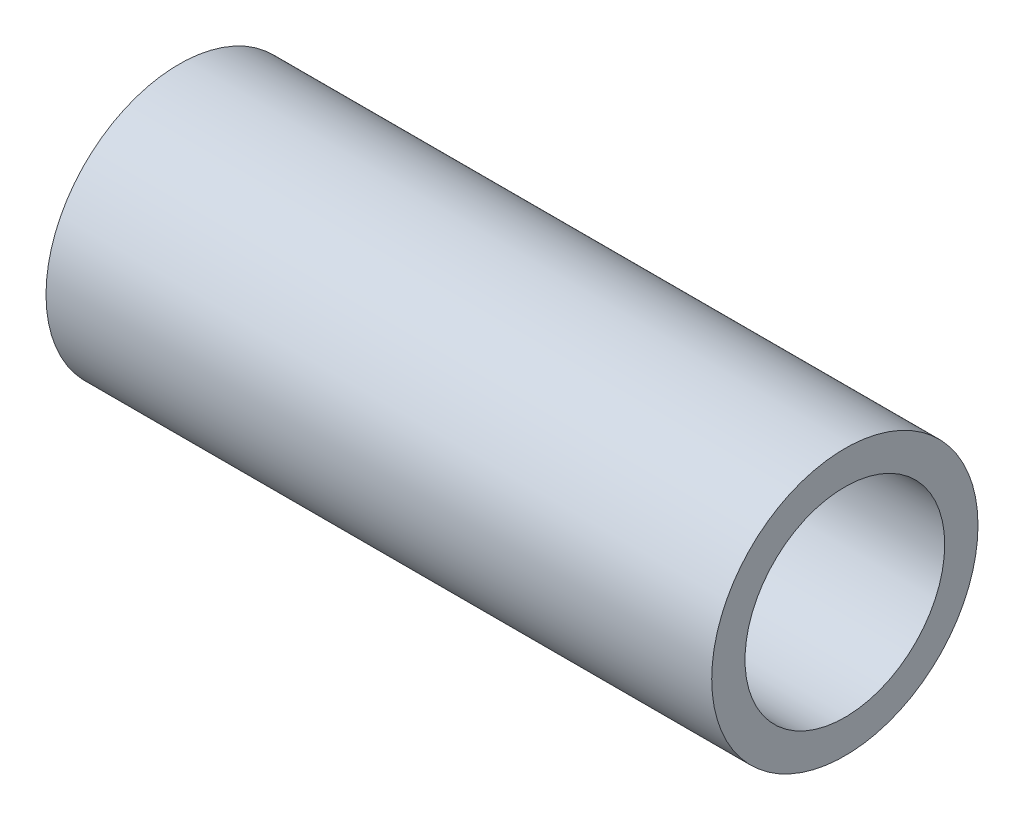
SolidWorks part; units mm, degrees
material "PTFE (general)"
ref_plane "Front Plane" through (0, 0, 0) normal (0, 0, 1) x (1, 0, 0)
ref_plane "Top Plane" through (0, 0, 0) normal (0, 1, 0) x (1, 0, 0)
ref_plane "Right Plane" through (0, 0, 0) normal (1, 0, 0) x (0, 0, -1)
sketch "Sketch1" plane through (0, 0, 0) normal (1, 0, 0) x (0, 0, -1)
  circle A0 centre (0, 0) radius 4.7625
  circle A1 centre (0, 0) radius 6.35
  dimension "D1" = 9.525
  dimension "D2" = 12.7
extrude "Boss-Extrude1" add sketch "Sketch1" along normal mid plane 31.75
